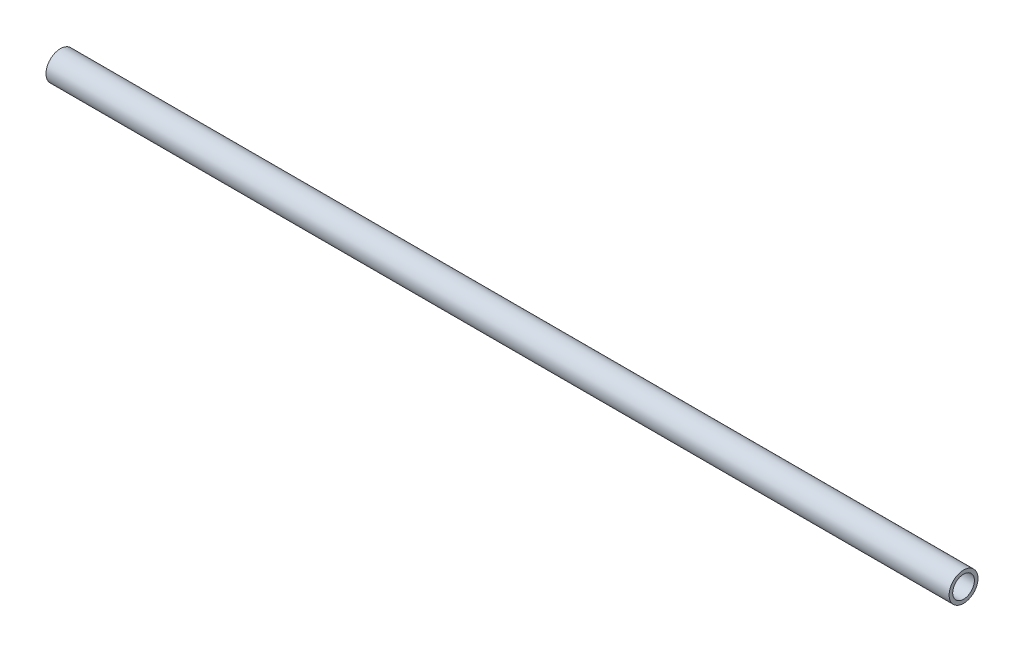
SolidWorks part; units mm, degrees
ref_plane "Front Plane" through (0, 0, 0) normal (0, 0, 1) x (1, 0, 0)
ref_plane "Top Plane" through (0, 0, 0) normal (0, 1, 0) x (1, 0, 0)
ref_plane "Right Plane" through (0, 0, 0) normal (1, 0, 0) x (0, 0, -1)
sketch "Sketch1" plane through (0, 0, 0) normal (1, 0, 0) x (0, 0, -1)
  circle A0 centre (0, 0) radius 3
  circle A1 centre (0, 0) radius 4
  dimension "D1" = 6
  dimension "D2" = 8
extrude "Boss-Extrude1" add sketch "Sketch1" along normal blind 250
